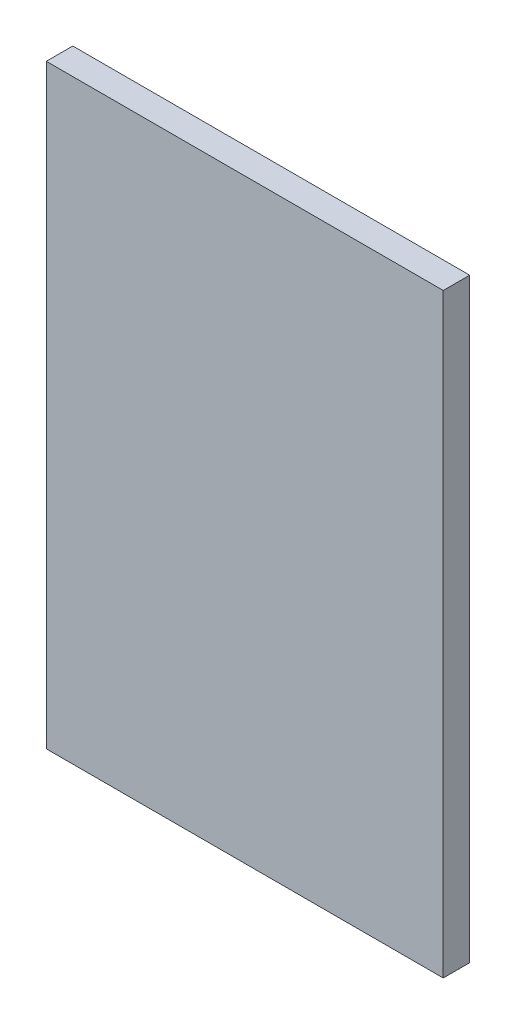
SolidWorks part; units mm, degrees
ref_plane "Alzado" through (0, 0, 0) normal (0, 0, 1) x (1, 0, 0)
ref_plane "Planta" through (0, 0, 0) normal (0, 1, 0) x (1, 0, 0)
ref_plane "Vista lateral" through (0, 0, 0) normal (1, 0, 0) x (0, 0, -1)
sketch "Croquis1" plane through (0, 0, 0) normal (0, 0, 1) x (1, 0, 0)
  line L1 (0, 0) -> (150, 0)
  line L2 (0, 0) -> (0, 225)
  line L3 (0, 225) -> (150, 225)
  line L4 (150, 0) -> (150, 225)
  dimension "D1" = 150
  dimension "D2" = 225
extrude "Saliente-Extruir1" add sketch "Croquis1" against normal blind 10
